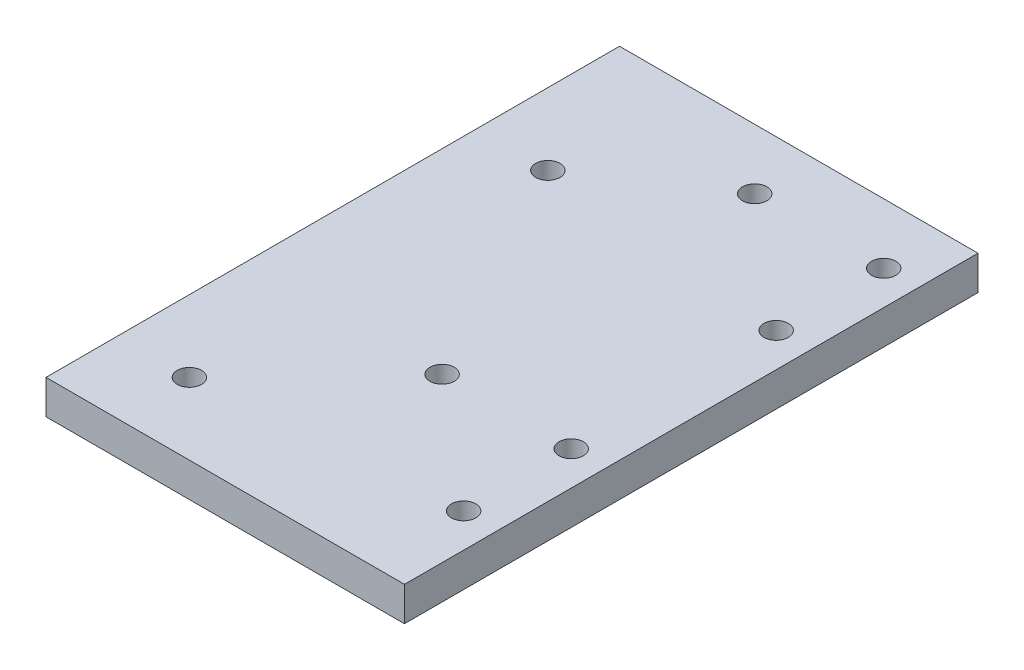
SolidWorks part; units mm, degrees
material "6061 Alloy"
ref_plane "Front Plane" through (0, 0, 0) normal (0, 0, 1) x (1, 0, 0)
ref_plane "Top Plane" through (0, 0, 0) normal (0, 1, 0) x (1, 0, 0)
ref_plane "Right Plane" through (0, 0, 0) normal (1, 0, 0) x (0, 0, -1)
sketch "Sketch1" plane through (0, 0, 0) normal (0, 1, 0) x (1, 0, 0)
  line L0 (0, 0) -> (0, 90)
  line L1 (0, 90) -> (50, 90)
  line L2 (50, 90) -> (50, 10)
  line L3 (50, 10) -> (20, 10)
  line L4 (20, 10) -> (20, 0)
  line L5 (0, 0) -> (20, 0)
  line L12 (20, 10) -> (0, 10)
  line L16 (20, 3.65) -> (20, 10) construction
  line L17 (14.5, 3.175) -> (5.5, 3.175) construction
  circle A5 centre (45.25, 81.6) radius 1.7
  circle A6 centre (14.5, 3.175) radius 1.55
  circle A7 centre (27.25, 81.6) radius 1.7
  circle A9 centre (5.5, 3.175) radius 1.55
  circle A15 centre (45.25, 23) radius 1.7
  circle A16 centre (45.25, 38) radius 1.7
  circle A17 centre (27.25, 38) radius 1.7
  circle A18 centre (45.25, 66.6) radius 1.7
  circle A19 centre (10, 20) radius 1.7
  circle A20 centre (10, 70) radius 1.7
  point P7 (0, 0)
  point P13 (45.25, 19.0561)
  point P16 (23.7294, 38)
  point P20 (10, 3.175)
  point P21 (10, 0)
  point P30 (0, 0)
  point P34 (25.6106, 38)
  point P36 (10, 10)
  point P37 (10, 20)
  point P39 (45.25, 23)
  dimension "D2" = 3.1
  dimension "D3" = 3.1
  dimension "D13" = 3.4
  dimension "D1" = 80
  dimension "D9" = 50
  dimension "D11" = 10
  dimension "D4" = 9
  dimension "D5" = 3.175
  dimension "D6" = 15
  dimension "D7" = 8.4
  dimension "D8" = 10
  dimension "D10" = 50
  dimension "D12" = 27.25
  dimension "D14" = 18
  dimension "D15" = 15
  dimension "D16" = 13
extrude "Boss-Extrude1" add sketch "Sketch1" along normal blind 4.7625 contours L12 L3 L2 L1 L0 A20 A19 A18 A17 A16 A15 A7 A5
equation "\"D3@Sketch1\"=\"D2@Sketch1\""
